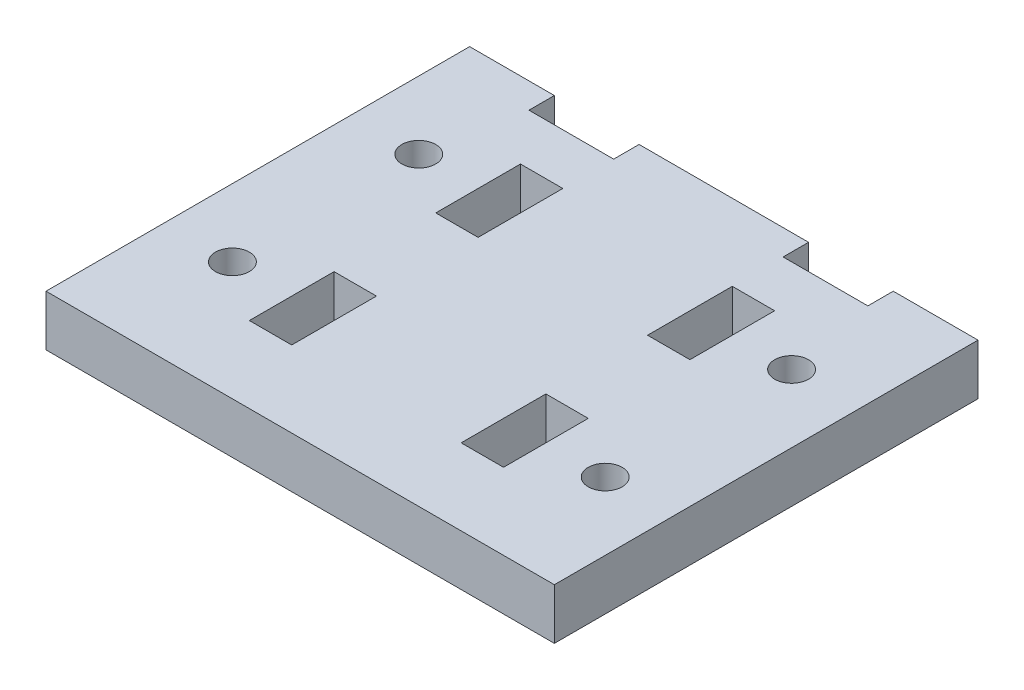
SolidWorks part; units mm, degrees
ref_plane "Front Plane" through (0, 0, 0) normal (0, 0, 1) x (1, 0, 0)
ref_plane "Top Plane" through (0, 0, 0) normal (0, 1, 0) x (1, 0, 0)
ref_plane "Right Plane" through (0, 0, 0) normal (1, 0, 0) x (0, 0, -1)
sketch "Sketch2" plane through (0, 0, 0) normal (0, 1, 0) x (1, 0, 0)
  line L0 (18.3739, 21.8704) -> (23.3739, 21.8704)
  line L1 (-21.6261, 30.8704) -> (-11.6261, 30.8704)
  line L2 (-21.6261, 30.8704) -> (-21.6261, -19.1296)
  line L3 (-21.6261, -19.1296) -> (38.3739, -19.1296)
  line L4 (38.3739, 30.8704) -> (38.3739, -19.1296)
  line L5 (-6.6261, 21.8704) -> (-1.6261, 21.8704)
  line L6 (-6.6261, 21.8704) -> (-6.6261, 11.8704)
  line L7 (-6.6261, 11.8704) -> (-1.6261, 11.8704)
  line L8 (-1.6261, 21.8704) -> (-1.6261, 11.8704)
  line L9 (18.3739, 21.8704) -> (18.3739, 11.8704)
  line L10 (18.3739, 11.8704) -> (23.3739, 11.8704)
  line L11 (23.3739, 21.8704) -> (23.3739, 11.8704)
  line L12 (-6.6261, -0.1296) -> (-1.6261, -0.1296)
  line L13 (-6.6261, -0.1296) -> (-6.6261, -10.1296)
  line L14 (-6.6261, -10.1296) -> (-1.6261, -10.1296)
  line L15 (-1.6261, -0.1296) -> (-1.6261, -10.1296)
  line L16 (18.3739, -0.1296) -> (23.3739, -0.1296)
  line L17 (18.3739, -0.1296) -> (18.3739, -10.1296)
  line L18 (18.3739, -10.1296) -> (23.3739, -10.1296)
  line L19 (23.3739, -0.1296) -> (23.3739, -10.1296)
  line L20 (-1.6261, 30.8704) -> (18.3739, 30.8704)
  line L22 (-11.6261, 30.8704) -> (-11.6261, 27.8704)
  line L23 (-11.6261, 27.8704) -> (-1.6261, 27.8704)
  line L24 (-1.6261, 30.8704) -> (-1.6261, 27.8704)
  line L25 (28.3739, 30.8704) -> (38.3739, 30.8704)
  line L26 (18.3739, 27.8704) -> (28.3739, 27.8704)
  line L27 (18.3739, 27.8704) -> (18.3739, 30.8704)
  line L29 (28.3739, 27.8704) -> (28.3739, 30.8704)
  circle A0 centre (-13.6261, 16.8704) radius 2
  circle A1 centre (-13.6261, -5.1296) radius 2
  circle A2 centre (30.3739, 16.8704) radius 2
  circle A3 centre (30.3739, -5.1296) radius 2
  point P36 (0, 0)
  point P37 (80.0631, 33.8516)
  dimension "D1" = 22
  dimension "D6" = 8
  dimension "D2" = 22
  dimension "D3" = 44
  dimension "D4" = 44
  dimension "D5" = 60
  dimension "D7" = 5
  dimension "D8" = 5
  dimension "D9" = 5
  dimension "D10" = 5
  dimension "D11" = 50
  dimension "D12" = 14
  dimension "D13" = 14
  dimension "D14" = 10
  dimension "D15" = 10
  dimension "D16" = 10
  dimension "D17" = 10
  dimension "D18" = 15
  dimension "D19" = 5
  dimension "D20" = 10
  dimension "D21" = 5
  dimension "D22" = 10
  dimension "D23" = 10
  dimension "D24" = 5
  dimension "D25" = 10
  dimension "D26" = 5
  dimension "D27" = 15
  dimension "D28" = 15
  dimension "D29" = 15
  dimension "D30" = 9
extrude "Boss-Extrude1" add sketch "Sketch2" along normal blind 6
